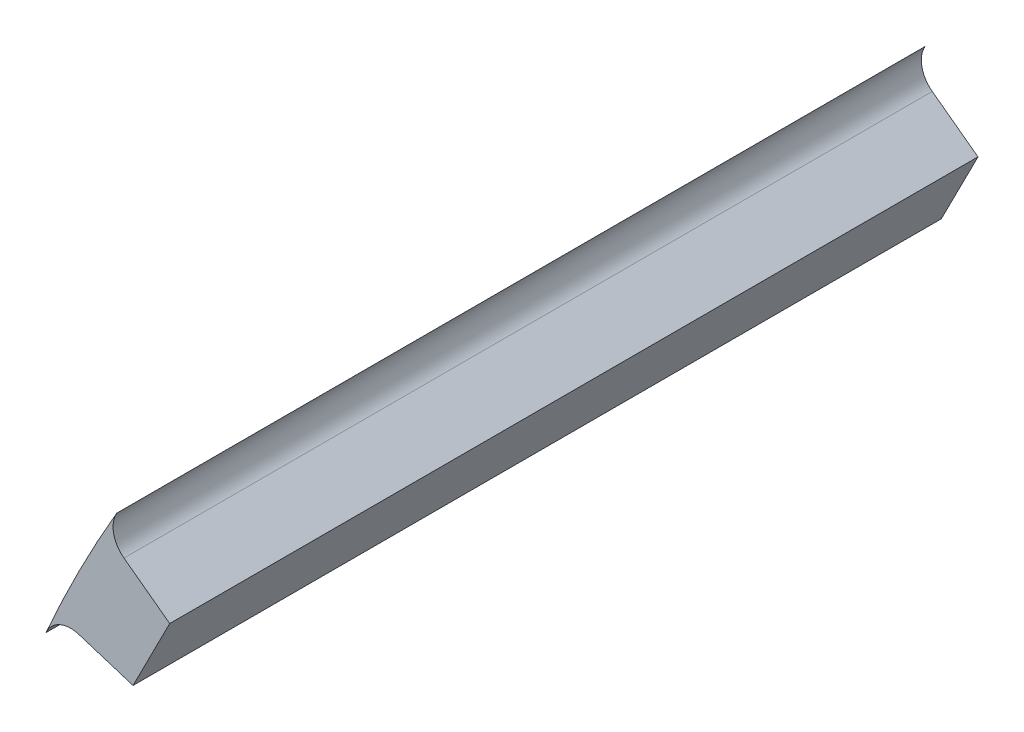
SolidWorks part; units mm, degrees
ref_plane "Front Plane" through (0, 0, 0) normal (0, 0, 1) x (1, 0, 0)
ref_plane "Top Plane" through (0, 0, 0) normal (0, 1, 0) x (1, 0, 0)
ref_plane "Right Plane" through (0, 0, 0) normal (1, 0, 0) x (0, 0, -1)
sketch "Sketch2" plane through (0, 0, -30) normal (0, 0, -1) x (-1, 0, 0)
  line L3 (44.5713, 20.6372) -> (42.5583, 20.001)
  line L4 (41.1963, 22.6741) -> (42.8942, 23.9287)
  line L5 (42.5583, 20.001) -> (41.1963, 22.6741)
  arc A2 (45.7884, 20.0854) -> (44.5713, 20.6372) centre (44.8726, 19.6837) ccw
  arc A3 (42.8942, 23.9287) -> (43.1632, 25.2377) centre (42.2999, 24.7329) ccw
  arc A4 (45.7884, 20.0854) -> (43.1632, 25.2377) centre (0, 0) ccw
extrude "Boss-Extrude1" add sketch "Sketch2" against normal blind 30
